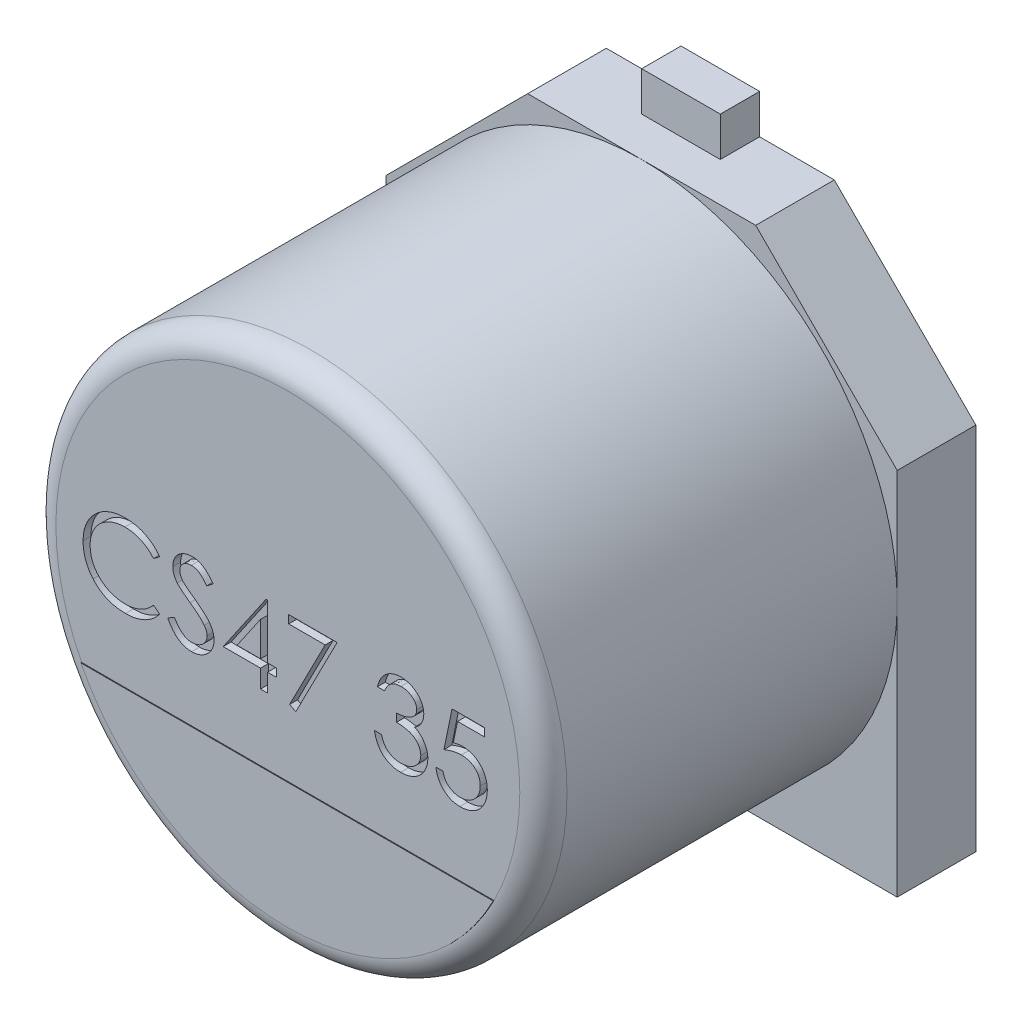
SolidWorks part; units mm, degrees
ref_plane "Front Plane" through (0, 0, 0) normal (0, 0, 1) x (1, 0, 0)
ref_plane "Top Plane" through (0, 0, 0) normal (0, 1, 0) x (1, 0, 0)
ref_plane "Right Plane" through (0, 0, 0) normal (1, 0, 0) x (0, 0, -1)
sketch "Sketch1" plane through (0, 0, 0) normal (0, 0, 1) x (1, 0, 0)
  line L1 (-3.25, 3.25) -> (3.25, 3.25)
  line L2 (-3.25, 3.25) -> (-3.25, -3.25)
  line L3 (-3.25, -3.25) -> (3.25, -3.25)
  line L4 (3.25, 3.25) -> (3.25, -3.25)
  line L5 (-3.25, 3.25) -> (3.25, -3.25) construction
  line L6 (-3.25, -3.25) -> (3.25, 3.25) construction
  point P0 (0, 0)
  dimension "D1" = 6.5
  dimension "D2" = 6.5
extrude "Boss-Extrude1" add sketch "Sketch1" along normal blind 1
sketch "Sketch2" plane through (0, 0, 1) normal (0, 0, 1) x (1, 0, 0)
  circle A0 centre (0, 0) radius 3.25
  dimension "D1" = 6.5
extrude "Boss-Extrude2" add sketch "Sketch2" along normal blind 4.5
chamfer "Chamfer1" distance 1.8 angle 45 2 edges at (3.25, 3.25, 0.5) (-3.25, 3.25, 0.5)
fillet "Fillet1" radius 0.3 1 edges at (3.25, 0, 5.5)
sketch "Sketch3" plane through (0, 0, 5.5) normal (0, 0, 1) x (1, 0, 0)
  line L1 (-2.6225, -1.3509) -> (2.6225, -1.3509)
  arc A1 (-2.6225, -1.3509) -> (2.6225, -1.3509) centre (0, 0) ccw
extrude "Boss-Extrude3" add sketch "Sketch3" along normal blind 0.01
sketch "Sketch4" plane through (0, 0, 0) normal (1, 0, 0) x (0, 0, -1)
  line L1 (0, 3.25) -> (-0.5, 3.25)
  line L2 (0, 3.25) -> (0, 3.75)
  line L3 (0, 3.75) -> (-0.5, 3.75)
  line L4 (-0.5, 3.25) -> (-0.5, 3.75)
  line L5 (0, -3.25) -> (-0.5, -3.25)
  line L6 (0, -3.25) -> (0, -3.75)
  line L7 (0, -3.75) -> (-0.5, -3.75)
  line L8 (-0.5, -3.25) -> (-0.5, -3.75)
  dimension "D1" = 0.5
  dimension "D2" = 0.5
  dimension "D3" = 0.5
  dimension "D4" = 0.5
extrude "Boss-Extrude4" add sketch "Sketch4" along normal blind 0.5 and the other way blind 0.5
sketch "Sketch5" plane through (0, 0, 5.5) normal (0, 0, 1) x (1, 0, 0)
  text T0 "CS47 35" font "Century Gothic" height 1
extrude "Cut-Extrude1" cut sketch "Sketch5" against normal blind 0.1
